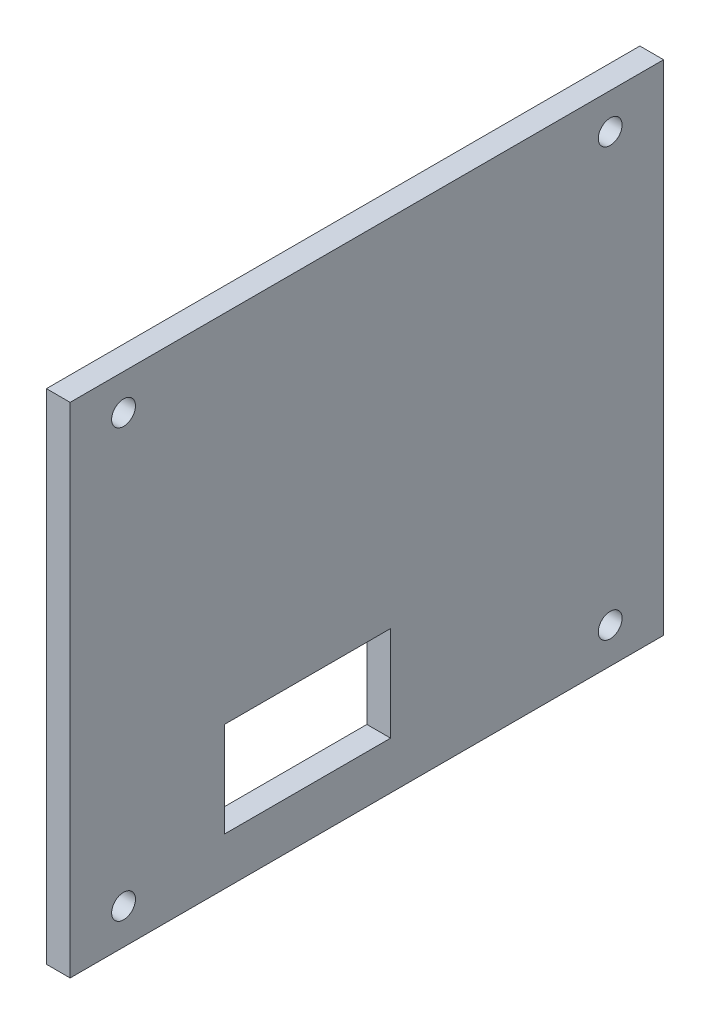
SolidWorks part; units mm, degrees
ref_plane "Front Plane" through (0, 0, 0) normal (0, 0, 1) x (1, 0, 0)
ref_plane "Top Plane" through (0, 0, 0) normal (0, 1, 0) x (1, 0, 0)
ref_plane "Right Plane" through (0, 0, 0) normal (1, 0, 0) x (0, 0, -1)
sketch "Sketch1" plane through (0, 0, 0) normal (1, 0, 0) x (0, 0, -1)
  line L1 (-25, -22) -> (25, -22)
  line L2 (-25, -22) -> (-25, 22)
  line L3 (-25, 22) -> (25, 22)
  line L4 (25, -22) -> (25, 22)
  line L5 (-25, -22) -> (25, 22) construction
  line L6 (-25, 22) -> (25, -22) construction
  point P0 (0, 0)
  point P6 (0, 0)
  point P7 (0, 0)
  point P8 (0, 0)
  point P9 (0, 0)
extrude "Boss-Extrude1" add sketch "Sketch1" along normal blind 2
sketch "Sketch2" plane through (0, 0, 0) normal (-1, 0, 0) x (0, 0, 1)
  line L9 (12, -17) -> (-2, -17)
  line L10 (12, -17) -> (12, -9)
  line L11 (12, -9) -> (-2, -9)
  line L12 (-2, -17) -> (-2, -9)
  circle A1 centre (20.4998, 18) radius 1.0036
  point P0 (0, 0)
extrude "Cut-Extrude1" cut sketch "Sketch2" against normal blind 2
pattern_linear "LPattern1" count 2 spacing 41 along (0, 0, -1) count 2 spacing 36 along (0, -1, 0) of "Cut-Extrude1"
sketch "Sketch6" plane through (2, 0, 0) normal (1, 0, 0) x (0, 0, -1)
  line L0 (-25, 22) -> (-25, 21.0016)
  line L1 (-25, 22) -> (-25, -22) construction
  line L2 (-25, 21.0016) -> (25, 21.0016)
  line L3 (25, -22) -> (25, 22) construction
  line L4 (25, 21.0016) -> (25, 22)
  line L5 (25, 22) -> (-25, 22)
extrude "Cut-Extrude2" cut sketch "Sketch6" against normal blind 5
sketch "Sketch7" plane through (2, 0, 0) normal (1, 0, 0) x (0, 0, -1)
  line L0 (-25, -22) -> (-25, -21.0008)
  line L1 (-25, 21.0016) -> (-25, -22) construction
  line L2 (-25, -21.0008) -> (25, -21.0008)
  line L3 (25, -22) -> (25, 21.0016) construction
  line L4 (25, -21.0008) -> (25, -22)
  line L5 (25, -22) -> (-25, -22)
extrude "Cut-Extrude3" cut sketch "Sketch7" against normal blind 5
